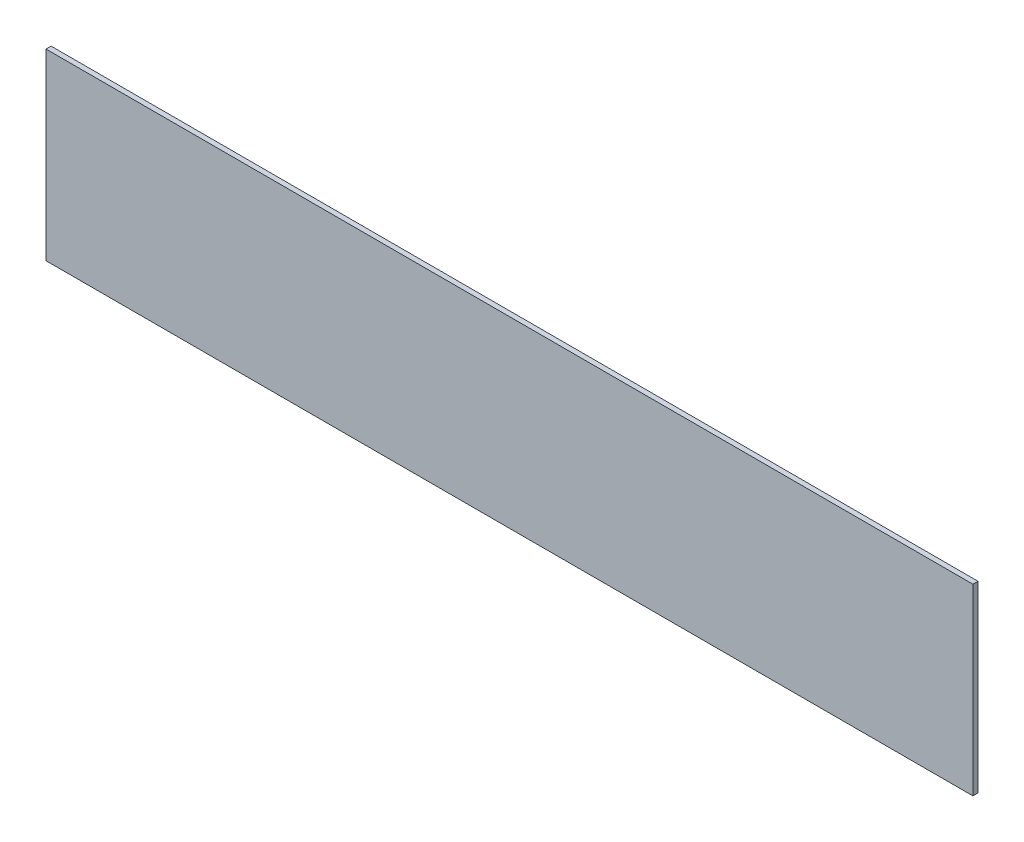
SolidWorks part; units mm, degrees
ref_plane "Front Plane" through (0, 0, 0) normal (0, 0, 1) x (1, 0, 0)
ref_plane "Top Plane" through (0, 0, 0) normal (0, 1, 0) x (1, 0, 0)
ref_plane "Right Plane" through (0, 0, 0) normal (1, 0, 0) x (0, 0, -1)
other "Configuration Table"
sketch "Sketch1" plane through (0, 0, 0) normal (0, 0, 1) x (1, 0, 0)
  line L1 (259, 582) -> (441, 582)
  line L2 (259, 582) -> (259, 618)
  line L3 (259, 618) -> (441, 618)
  line L4 (441, 582) -> (441, 618)
extrude "TOPPING_klape_alt1_kulp_cukuru_1" add sketch "Sketch1" along normal blind 1 from offset 26 separate body
